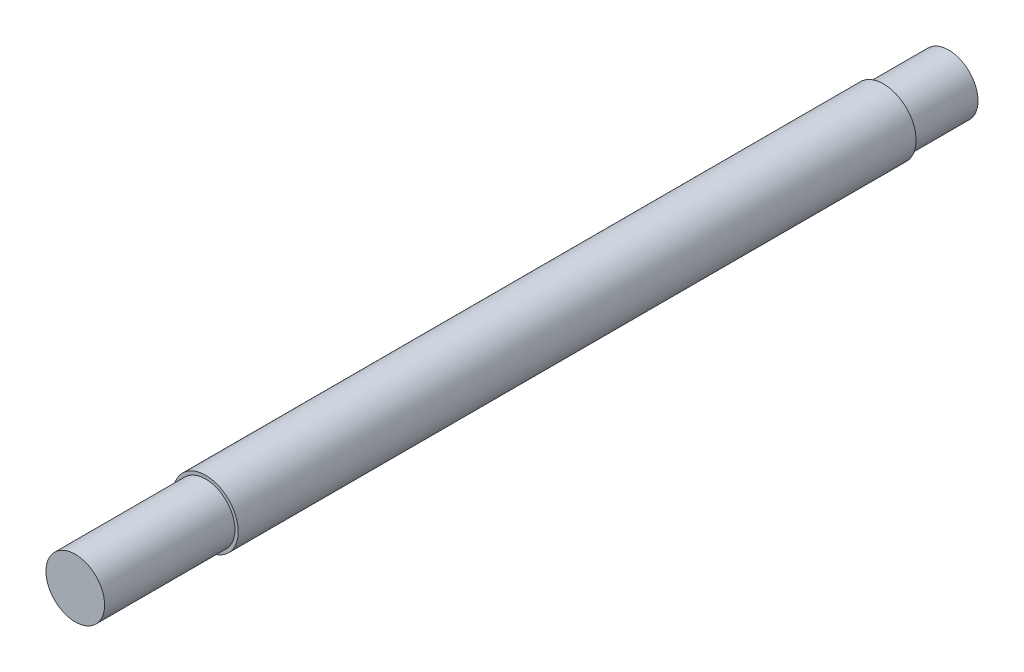
SolidWorks part; units mm, degrees
material "铸造碳钢"
ref_plane "前视基准面" through (0, 0, 0) normal (0, 0, 1) x (1, 0, 0)
ref_plane "上视基准面" through (0, 0, 0) normal (0, 1, 0) x (1, 0, 0)
ref_plane "右视基准面" through (0, 0, 0) normal (1, 0, 0) x (0, 0, -1)
sketch "草图1" plane through (0, 0, 0) normal (0, 0, 1) x (1, 0, 0)
  circle A0 centre (0, 0) radius 5
  dimension "D1" = 10
extrude "凸台-拉伸1" add sketch "草图1" along normal mid plane 104
sketch "草图2" plane through (0, 0, -52) normal (0, 0, -1) x (-1, 0, 0)
  circle A0 centre (0, 0) radius 4.5
  dimension "D1" = 9
extrude "凸台-拉伸2" add sketch "草图2" along normal blind 10
sketch "草图3" plane through (0, 0, 52) normal (0, 0, 1) x (1, 0, 0)
  circle A0 centre (0, 0) radius 4.5
  dimension "D1" = 9
extrude "凸台-拉伸3" add sketch "草图3" along normal blind 20
